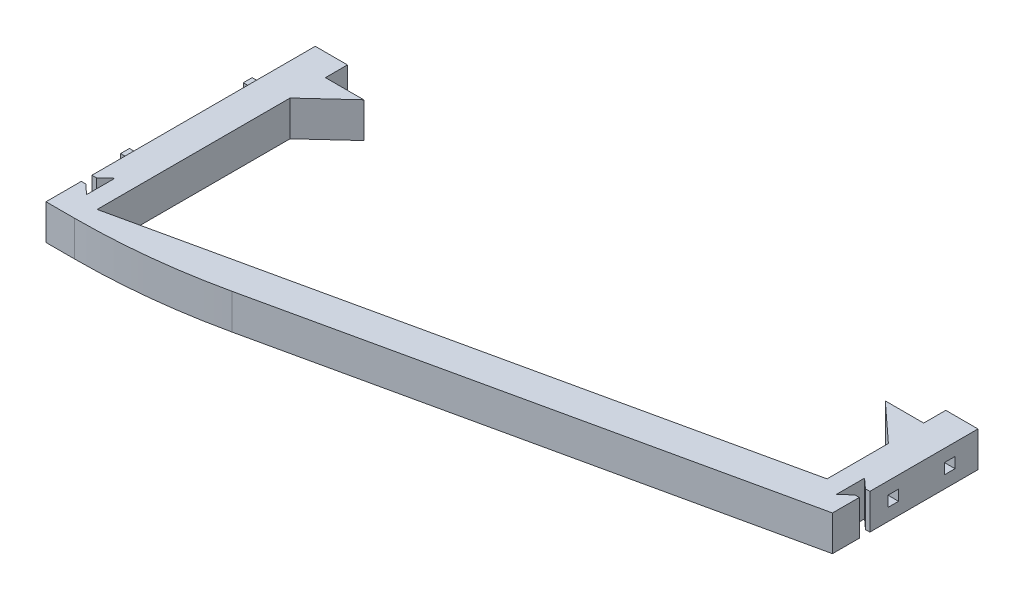
SolidWorks part; units mm, degrees
ref_plane "Přední rovina" through (0, 0, 0) normal (0, 0, 1) x (1, 0, 0)
ref_plane "Horní rovina" through (0, 0, 0) normal (0, 1, 0) x (1, 0, 0)
ref_plane "Pravá rovina" through (0, 0, 0) normal (1, 0, 0) x (0, 0, -1)
sketch "Skica1" plane through (0, 0, 0) normal (0, 1, 0) x (1, 0, 0)
  line L0 (0, 0) -> (0, -66)
  line L1 (0, -66) -> (150.15, -32.97)
  line L2 (150.15, -32.97) -> (150.15, 0)
  line L3 (150.15, 0) -> (142.85, 0)
  line L4 (142.85, 0) -> (142.85, -26.8965)
  line L5 (142.85, -26.8965) -> (7.3, -56.7148)
  line L6 (7.3, -56.7148) -> (7.3, 0)
  line L7 (7.3, 0) -> (0, 0)
  dimension "D1" = 7.3
  dimension "D2" = 7.3
  dimension "D3" = 66
  dimension "D4" = 7.5
  dimension "D5" = 150.15
  dimension "D6" = 32.97
extrude "Přidat vysunutím1" add sketch "Skica1" along normal blind 8
sketch "Skica2" plane through (0, 8, 0) normal (0, 1, 0) x (1, 0, 0)
  line L5 (0, -50.6) -> (1, -50.6)
  line L6 (0, 0) -> (0, -66) construction
  line L7 (1, -50.6) -> (3.2, -48.6)
  line L8 (3.2, -48.6) -> (3.2, -55)
  line L9 (3.2, -55) -> (1, -53)
  line L10 (1, -53) -> (0, -53)
  line L11 (0, -53) -> (0, -50.6)
  dimension "D1" = 6.4
  dimension "D2" = 2.4
  dimension "D3" = 1
  dimension "D4" = 1
  dimension "D5" = 2
  dimension "D6" = 3.2
  dimension "D7" = 11
extrude "Odebrat vysunutím1" cut sketch "Skica2" against normal through all
sketch "Skica3" plane through (0, 0, 0) normal (-1, 0, 0) x (0, 0, 1)
  line L0 (0, 8) -> (0, 0) construction
  line L1 (10.3, 5) -> (12.3, 5)
  line L2 (10.3, 5) -> (10.3, 3)
  line L3 (10.3, 3) -> (12.3, 3)
  line L4 (12.3, 5) -> (12.3, 3)
  line L5 (38.1, 5) -> (40.1, 5)
  line L6 (38.1, 5) -> (38.1, 3)
  line L7 (38.1, 3) -> (40.1, 3)
  line L8 (40.1, 5) -> (40.1, 3)
  line L17 (0, 8) -> (50.6, 8) construction
  point P16 (10.3, 4)
  dimension "D1" = 10.3
  dimension "D2" = 2
  dimension "D3" = 2
  dimension "D4" = 3
  dimension "D5" = 2
  dimension "D6" = 2
  dimension "D7" = 3
  dimension "D8" = 25.8
extrude "Přidat vysunutím2" add sketch "Skica3" along normal blind 4
sketch "Skica5" plane through (0, 8, 0) normal (0, 1, 0) x (1, 0, 0)
  line L0 (0, 0) -> (0, -50.6) construction
  line L1 (0, -5) -> (16, -5)
  line L2 (0, -5) -> (0, -13)
  line L3 (0, -13) -> (16, -13)
  line L4 (16, -5) -> (16, -13)
  line L5 (150.15, -32.97) -> (150.15, 0) construction
  line L6 (150.15, -5) -> (134.15, -5)
  line L7 (150.15, -5) -> (150.15, -13)
  line L8 (150.15, -13) -> (134.15, -13)
  line L9 (134.15, -5) -> (134.15, -13)
  line L10 (150.15, 0) -> (142.85, 0) construction
  line L11 (7.3, 0) -> (0, 0) construction
  dimension "D1" = 8
  dimension "D2" = 8
  dimension "D3" = 16
  dimension "D4" = 16
  dimension "D5" = 5
  dimension "D6" = 5
extrude "Přidat vysunutím3" add sketch "Skica5" against normal blind 8
sketch "Skica7" plane through (0, 0, 0) normal (0, -1, 0) x (1, 0, 0)
  line L0 (7.3, 13) -> (16, 5)
  line L1 (16, 5) -> (16, 13)
  line L2 (16, 13) -> (7.3, 13)
  line L3 (134.15, 5) -> (134.15, 13)
  line L4 (134.15, 13) -> (142.85, 13)
  line L5 (142.85, 13) -> (134.15, 5)
extrude "Odebrat vysunutím4" cut sketch "Skica7" against normal through all
sketch "Skica4" plane through (150.15, 0, 0) normal (1, 0, 0) x (0, 0, -1)
  line L0 (-32.97, 8) -> (0, 8) construction
  line L5 (-20.4, 5.2) -> (-18, 5.2)
  line L6 (-20.4, 5.2) -> (-20.4, 2.8)
  line L7 (-20.4, 2.8) -> (-18, 2.8)
  line L8 (-18, 5.2) -> (-18, 2.8)
  line L9 (-7.6, 5.2) -> (-5.2, 5.2)
  line L10 (-7.6, 5.2) -> (-7.6, 2.8)
  line L11 (-7.6, 2.8) -> (-5.2, 2.8)
  line L12 (-5.2, 5.2) -> (-5.2, 2.8)
  line L14 (0, 8) -> (0, 0) construction
  point P16 (-18, 4)
  dimension "D1" = 2.4
  dimension "D2" = 2.4
  dimension "D3" = 2.8
  dimension "D7" = 2.4
  dimension "D8" = 2.4
  dimension "D9" = 2.8
  dimension "D10" = 5.2
  dimension "D12" = 10.4
extrude "Odebrat vysunutím2" cut sketch "Skica4" against normal blind 4.4
sketch "Skica8" plane through (0, 8, 0) normal (0, 1, 0) x (1, 0, 0)
  line L6 (150.15, -24.5) -> (149.15, -24.5)
  line L7 (150.15, -32.97) -> (150.15, 0) construction
  line L8 (149.15, -24.5) -> (146.95, -22.5)
  line L9 (146.95, -22.5) -> (146.95, -28.9)
  line L10 (146.95, -28.9) -> (149.15, -26.9)
  line L11 (150.15, -26.9) -> (150.15, -24.5)
  line L12 (149.15, -26.9) -> (150.15, -26.9)
  line L13 (150.15, 0) -> (142.85, 0) construction
  point P10 (146.5, 0)
  dimension "D1" = 6.4
  dimension "D2" = 1
  dimension "D3" = 2.4
  dimension "D4" = 2
  dimension "D5" = 3.2
  dimension "D6" = 22.5
  dimension "D7" = 1
extrude "Odebrat vysunutím5" cut sketch "Skica8" against normal through all
sketch "Skica9" plane through (0, 8, 0) normal (0, 1, 0) x (1, 0, 0)
  line L0 (0, -61) -> (22.7293, -61)
  line L1 (0, -53) -> (0, -66) construction
  line L2 (0, -66) -> (150.15, -32.97) construction
  line L3 (22.7293, -61) -> (0, -66)
  line L4 (0, -66) -> (0, -61)
  dimension "D1" = 5
extrude "Odebrat vysunutím6" cut sketch "Skica9" against normal through all
fillet "Zaoblit1" radius 150 1 edges at (22.7293, 4, 61)
